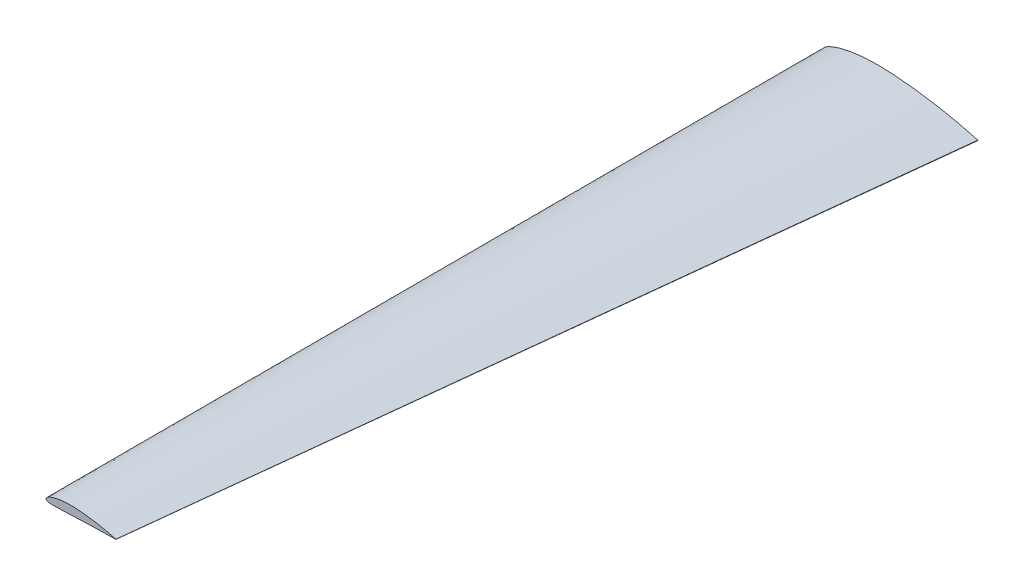
SolidWorks part; units mm, degrees
ref_plane "Front Plane" through (0, 0, 0) normal (0, 0, 1) x (1, 0, 0)
ref_plane "Top Plane" through (0, 0, 0) normal (0, 1, 0) x (1, 0, 0)
ref_plane "Right Plane" through (0, 0, 0) normal (1, 0, 0) x (0, 0, -1)
curve "Curve1"
  spline degree 3 poles (25.4, 0.033, 0) (24.9771, 0.1481, 0) (24.1334, 0.3778, 0) (22.4431, 0.7955, 0) (20.3293, 1.2569, 0) (17.7869, 1.7118, 0) (15.2464, 2.0846, 0) (12.7045, 2.3505, 0) (10.1628, 2.5164, 0) (8.041, 2.5181, 0) (6.3469, 2.4009, 0) (5.0745, 2.2465, 0) (3.7995, 2.0188, 0) (2.7428, 1.745, 0) (1.8961, 1.4685, 0) (1.2577, 1.2074, 0) (0.7129, 0.9251, 0) (0.2401, 0.5874, 0) (-0.1715, 0.0442, 0) (0.2727, -0.3711, 0) (0.7261, -0.5342, 0) (1.266, -0.6443, 0) (1.9036, -0.7002, 0) (2.7513, -0.7398, 0) (3.8103, -0.7368, 0) (5.0806, -0.7013, 0) (6.3499, -0.6336, 0) (8.0433, -0.5544, 0) (10.1596, -0.4528, 0) (12.7001, -0.3574, 0) (15.2397, -0.2514, 0) (17.7796, -0.1611, 0) (20.3198, -0.0947, 0) (22.4366, -0.061, 0) (24.13, -0.0388, 0) (24.9767, -0.035, 0) (25.4, -0.033, 0) knots 0 0 0 0 0.025305 0.050488 0.10052 0.150191 0.199587 0.24874 0.297716 0.346601 0.371103 0.395726 0.42057 0.445825 0.458702 0.47192 0.485786 0.493461 0.506863 0.516148 0.522766 0.535269 0.547551 0.559786 0.584229 0.608681 0.633151 0.657622 0.706558 0.755482 0.804406 0.85332 0.902221 0.951113 0.975557 1 1 1 1
sketch "Sketch1" plane through (0, 0, 0) normal (0, 0, 1) x (1, 0, 0)
  arc A0 (100.041, 0.1301) -> (100.041, -0.1301) centre (100.0005, 0) cw
  spline S1 degree 3 poles (100.041, 0.1301) (98.3753, 0.5835) (95.0521, 1.4881) (88.3947, 3.133) (80.0695, 4.9504) (70.0557, 6.7419) (60.0498, 8.2104) (50.0382, 9.2579) (40.0275, 9.9112) (31.6705, 9.9178) (24.9979, 9.4562) (19.9867, 8.8481) (14.9646, 7.9514) (10.803, 6.873) (7.4681, 5.7839) (4.9535, 4.7556) (2.8079, 3.6437) (0.9456, 2.3135) (-0.6757, 0.1743) (1.0742, -1.4618) (2.8598, -2.104) (4.9863, -2.5375) (7.4977, -2.7579) (10.8364, -2.9138) (15.0072, -2.9022) (20.0104, -2.7622) (25.01, -2.4956) (31.6794, -2.1837) (40.0148, -1.7834) (50.0208, -1.4075) (60.0235, -0.9901) (70.0273, -0.6346) (80.0318, -0.3732) (88.3693, -0.2404) (95.0388, -0.153) (98.3736, -0.1377) (100.041, -0.1301) knots 0 0 0 0 0.025305 0.050488 0.10052 0.150191 0.199587 0.24874 0.297716 0.346601 0.371103 0.395726 0.42057 0.445825 0.458702 0.47192 0.485786 0.493461 0.506863 0.516148 0.522766 0.535269 0.547551 0.559786 0.584229 0.608681 0.633151 0.657622 0.706558 0.755482 0.804406 0.85332 0.902221 0.951113 0.975557 1 1 1 1
ref_plane "Plane1" through (0, 0, 500) normal (0, 0, 1) x (1, 0, 0)
sketch "Sketch2" plane through (0, 0, 500) normal (0, 0, 1) x (1, 0, 0)
  arc A0 (45, 0.0585) -> (45, -0.0585) centre (44.9843, 0) cw
  spline S1 degree 3 poles (45, 0.0585) (44.2508, 0.2625) (42.7559, 0.6694) (39.7613, 1.4093) (36.0165, 2.2268) (31.5122, 3.0326) (27.0113, 3.6932) (22.508, 4.1644) (18.005, 4.4582) (14.2459, 4.4612) (11.2444, 4.2535) (8.9903, 3.98) (6.7313, 3.5767) (4.8594, 3.0916) (3.3593, 2.6017) (2.2282, 2.1392) (1.2631, 1.639) (0.4253, 1.0407) (-0.3039, 0.0784) (0.4832, -0.6575) (1.2864, -0.9464) (2.2429, -1.1414) (3.3726, -1.2405) (4.8744, -1.3107) (6.7505, -1.3054) (9.001, -1.2425) (11.2499, -1.1225) (14.2499, -0.9822) (17.9993, -0.8022) (22.5001, -0.6331) (26.9995, -0.4454) (31.4994, -0.2855) (35.9996, -0.1678) (39.7499, -0.1081) (42.7499, -0.0688) (44.25, -0.0619) (45, -0.0585) knots 0 0 0 0 0.025305 0.050488 0.10052 0.150191 0.199587 0.24874 0.297716 0.346601 0.371103 0.395726 0.42057 0.445825 0.458702 0.47192 0.485786 0.493461 0.506863 0.516148 0.522766 0.535269 0.547551 0.559786 0.584229 0.608681 0.633151 0.657622 0.706558 0.755482 0.804406 0.85332 0.902221 0.951113 0.975557 1 1 1 1
loft "Loft1" add profiles "Sketch2", "Sketch1"
